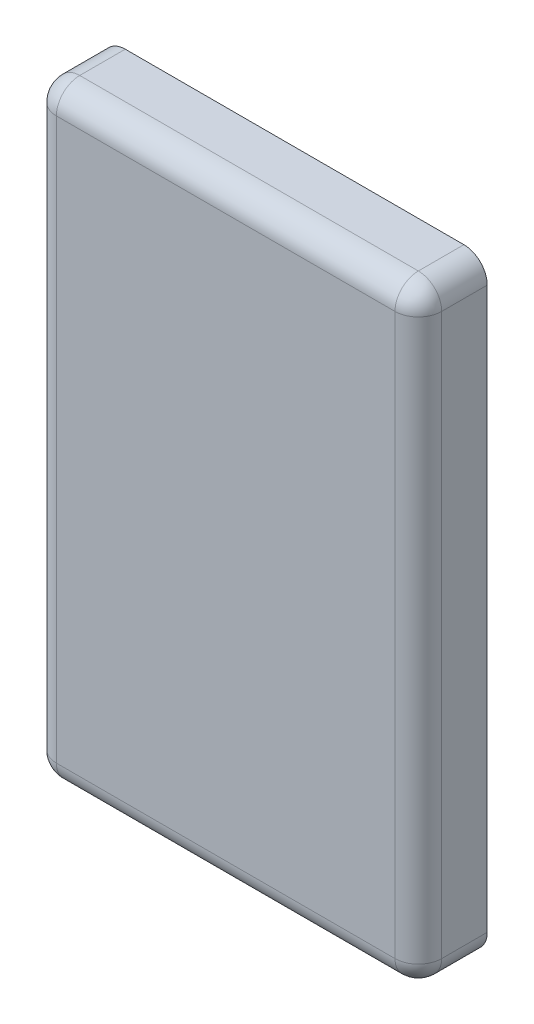
SolidWorks part; units mm, degrees
ref_plane "Alzado" through (0, 0, 0) normal (1, 0, 0) x (0, 1, 0)
ref_plane "Planta" through (0, 0, 0) normal (0, 0, 1) x (0, 1, 0)
ref_plane "Vista lateral" through (0, 0, 0) normal (0, 1, 0) x (-1, 0, 0)
sketch "Croquis1" plane through (0, 0, 0) normal (0, 0, 1) x (0, 1, 0)
  line L1 (-260, -165) -> (260, -165)
  line L2 (-260, -165) -> (-260, 165)
  line L3 (-260, 165) -> (260, 165)
  line L4 (260, -165) -> (260, 165)
  line L5 (-260, -165) -> (260, 165) construction
  line L6 (-260, 165) -> (260, -165) construction
  point P0 (0, 0)
  dimension "D1" = 520
  dimension "D2" = 330
extrude "Saliente-Extruir1" add sketch "Croquis1" along normal blind 9
sketch "Croquis2" plane through (0, 0, 9) normal (0, 0, 1) x (1, 0, 0)
  line L4 (165, 260) -> (-165, 260)
  line L5 (-165, 260) -> (-165, -260)
  line L6 (-165, -260) -> (165, -260)
  line L7 (165, -260) -> (165, 260)
  line L8 (165, 260) -> (-165, 260)
  line L9 (-165, 260) -> (-165, -260)
  line L10 (-165, -260) -> (165, -260)
  line L11 (165, -260) -> (165, 260)
  dimension "D1" = 0
extrude "Saliente-Extruir2" add sketch "Croquis2" along normal blind 50
fillet "Redondeo1" radius 20 8 edges at (-165, -260, 29.5) (-165, 260, 29.5) (-165, 0, 59) (0, -260, 59) (0, 260, 59) (165, 260, 29.5) (165, -260, 29.5) (165, 0, 59)
